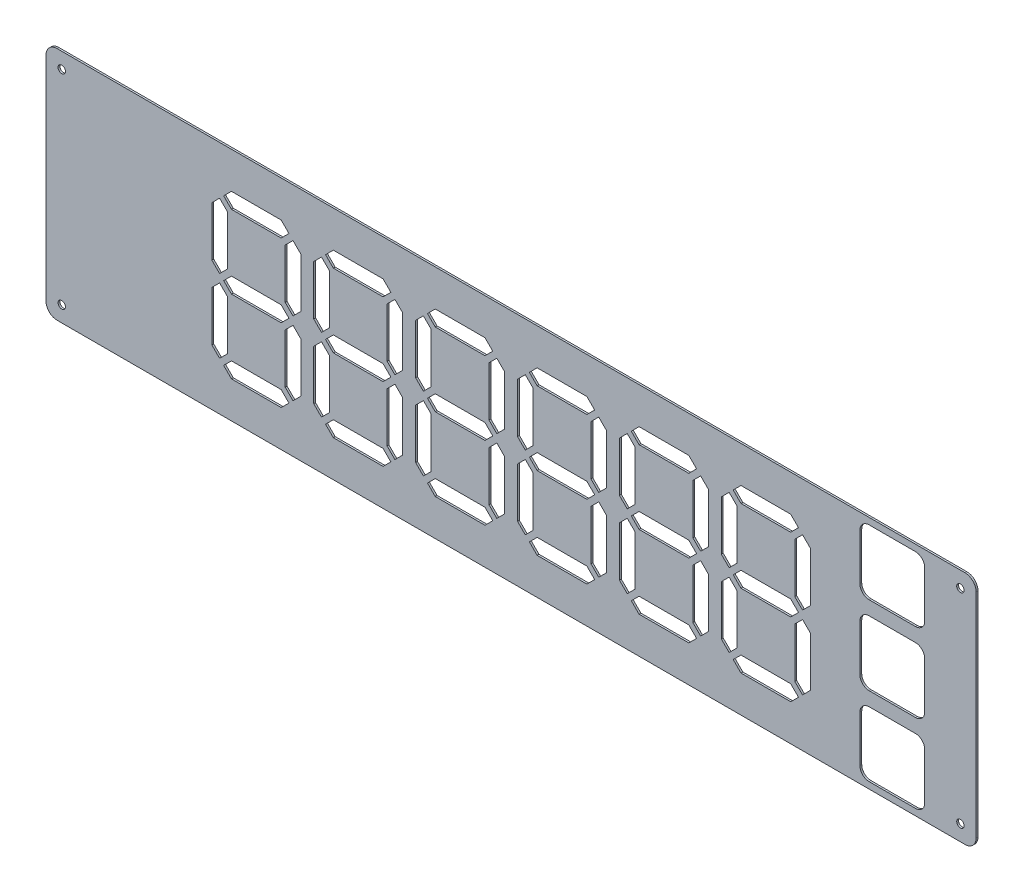
SolidWorks part; units mm, degrees
ref_plane "Plan de face" through (0, 0, 0) normal (0, 0, 1) x (1, 0, 0)
ref_plane "Plan de dessus" through (0, 0, 0) normal (0, 1, 0) x (1, 0, 0)
ref_plane "Plan de droite" through (0, 0, 0) normal (1, 0, 0) x (0, 0, -1)
sketch "Esquisse1" plane through (0, 0, 0) normal (0, 0, 1) x (1, 0, 0)
  line L0 (-107.7211, 8.5372) -> (517.2789, 8.5372) construction
  line L1 (204.7789, 142.0715) -> (204.7789, -117.1883) construction
  line L2 (694.7789, 135.5372) -> (-285.2211, 135.5372)
  line L7 (699.6693, -115.1854) -> (-290.1116, 132.2598) construction
  line L8 (699.6693, 132.2598) -> (-290.1116, -115.1854) construction
  line L9 (-297.2211, -106.4628) -> (-297.2211, 123.5372)
  line L10 (694.7789, -118.4628) -> (-285.2211, -118.4628)
  line L11 (706.7789, -106.4628) -> (706.7789, 123.5372)
  line L20 (-34.9839, 87.7798) -> (-43.3839, 96.1798)
  line L21 (-43.3839, 96.1798) -> (-97.0584, 96.1798)
  line L22 (-97.0584, 96.1798) -> (-105.4584, 87.7798)
  line L23 (-105.4584, 87.7798) -> (-97.0584, 79.3798)
  line L24 (-97.0584, 79.3798) -> (-43.3839, 79.3798)
  line L25 (-43.3839, 79.3798) -> (-34.9839, 87.7798)
  line L56 (-34.9839, -70.7055) -> (-43.3839, -62.3055)
  line L57 (-43.3839, -62.3055) -> (-97.0584, -62.3055)
  line L58 (-97.0584, -62.3055) -> (-105.4584, -70.7055)
  line L59 (-105.4584, -70.7055) -> (-97.0584, -79.1055)
  line L60 (-97.0584, -79.1055) -> (-43.3839, -79.1055)
  line L61 (-43.3839, -79.1055) -> (-34.9839, -70.7055)
  line L62 (-109.8425, 4.1531) -> (-118.2425, -4.2469)
  line L63 (-118.2425, -4.2469) -> (-118.2425, -57.9214)
  line L64 (-118.2425, -57.9214) -> (-109.8425, -66.3214)
  line L65 (-109.8425, -66.3214) -> (-101.4425, -57.9214)
  line L66 (-101.4425, -57.9214) -> (-101.4425, -4.2469)
  line L67 (-101.4425, -4.2469) -> (-109.8425, 4.1531)
  line L68 (-30.5998, 4.1531) -> (-38.9998, -4.2469)
  line L69 (-38.9998, -4.2469) -> (-38.9998, -57.9214)
  line L70 (-38.9998, -57.9214) -> (-30.5998, -66.3214)
  line L71 (-30.5998, -66.3214) -> (-22.1998, -57.9214)
  line L72 (-22.1998, -57.9214) -> (-22.1998, -4.2469)
  line L73 (-22.1998, -4.2469) -> (-30.5998, 4.1531)
  line L74 (-30.5998, 83.3957) -> (-38.9998, 74.9957)
  line L75 (-38.9998, 74.9957) -> (-38.9998, 21.3212)
  line L76 (-38.9998, 21.3212) -> (-30.5998, 12.9212)
  line L77 (-30.5998, 12.9212) -> (-22.1998, 21.3212)
  line L78 (-22.1998, 21.3212) -> (-22.1998, 74.9957)
  line L79 (-22.1998, 74.9957) -> (-30.5998, 83.3957)
  line L80 (-34.9839, 8.5372) -> (-43.3839, 16.9372)
  line L81 (-43.3839, 16.9372) -> (-97.0584, 16.9372)
  line L82 (-97.0584, 16.9372) -> (-105.4584, 8.5372)
  line L83 (-105.4584, 8.5372) -> (-97.0584, 0.1372)
  line L84 (-97.0584, 0.1372) -> (-43.3839, 0.1372)
  line L85 (-43.3839, 0.1372) -> (-34.9839, 8.5372)
  line L86 (-109.8425, 83.3957) -> (-118.2425, 74.9957)
  line L87 (-118.2425, 74.9957) -> (-118.2425, 21.3212)
  line L88 (-118.2425, 21.3212) -> (-109.8425, 12.9212)
  line L89 (-109.8425, 12.9212) -> (-101.4425, 21.3212)
  line L90 (-101.4425, 21.3212) -> (-101.4425, 74.9957)
  line L91 (-101.4425, 74.9957) -> (-109.8425, 83.3957)
  line L302 (515.0161, -70.7055) -> (506.6161, -62.3055)
  line L303 (506.6161, -62.3055) -> (452.9416, -62.3055)
  line L304 (452.9416, -62.3055) -> (444.5416, -70.7055)
  line L305 (444.5416, -70.7055) -> (452.9416, -79.1055)
  line L306 (452.9416, -79.1055) -> (506.6161, -79.1055)
  line L307 (506.6161, -79.1055) -> (515.0161, -70.7055)
  line L308 (519.4002, 4.1531) -> (511.0002, -4.2469)
  line L309 (511.0002, -4.2469) -> (511.0002, -57.9214)
  line L310 (511.0002, -57.9214) -> (519.4002, -66.3214)
  line L311 (519.4002, -66.3214) -> (527.8002, -57.9214)
  line L312 (527.8002, -57.9214) -> (527.8002, -4.2469)
  line L313 (527.8002, -4.2469) -> (519.4002, 4.1531)
  line L314 (519.4002, 83.3957) -> (511.0002, 74.9957)
  line L315 (511.0002, 74.9957) -> (511.0002, 21.3212)
  line L316 (511.0002, 21.3212) -> (519.4002, 12.9212)
  line L317 (519.4002, 12.9212) -> (527.8002, 21.3212)
  line L318 (527.8002, 21.3212) -> (527.8002, 74.9957)
  line L319 (527.8002, 74.9957) -> (519.4002, 83.3957)
  line L320 (515.0161, 8.5372) -> (506.6161, 16.9372)
  line L321 (506.6161, 16.9372) -> (452.9416, 16.9372)
  line L322 (452.9416, 16.9372) -> (444.5416, 8.5372)
  line L323 (444.5416, 8.5372) -> (452.9416, 0.1372)
  line L324 (452.9416, 0.1372) -> (506.6161, 0.1372)
  line L325 (506.6161, 0.1372) -> (515.0161, 8.5372)
  line L326 (515.0161, 87.7798) -> (506.6161, 96.1798)
  line L327 (506.6161, 96.1798) -> (452.9416, 96.1798)
  line L328 (452.9416, 96.1798) -> (444.5416, 87.7798)
  line L329 (444.5416, 87.7798) -> (452.9416, 79.3798)
  line L330 (452.9416, 79.3798) -> (506.6161, 79.3798)
  line L331 (506.6161, 79.3798) -> (515.0161, 87.7798)
  line L332 (440.1575, 83.3957) -> (431.7575, 74.9957)
  line L333 (431.7575, 74.9957) -> (431.7575, 21.3212)
  line L334 (431.7575, 21.3212) -> (440.1575, 12.9212)
  line L335 (440.1575, 12.9212) -> (448.5575, 21.3212)
  line L336 (448.5575, 21.3212) -> (448.5575, 74.9957)
  line L337 (448.5575, 74.9957) -> (440.1575, 83.3957)
  line L338 (440.1575, 4.1531) -> (431.7575, -4.2469)
  line L339 (431.7575, -4.2469) -> (431.7575, -57.9214)
  line L340 (431.7575, -57.9214) -> (440.1575, -66.3214)
  line L341 (440.1575, -66.3214) -> (448.5575, -57.9214)
  line L342 (448.5575, -57.9214) -> (448.5575, -4.2469)
  line L343 (448.5575, -4.2469) -> (440.1575, 4.1531)
  line L344 (405.0161, -70.7055) -> (396.6161, -62.3055)
  line L345 (396.6161, -62.3055) -> (342.9416, -62.3055)
  line L346 (342.9416, -62.3055) -> (334.5416, -70.7055)
  line L347 (334.5416, -70.7055) -> (342.9416, -79.1055)
  line L348 (342.9416, -79.1055) -> (396.6161, -79.1055)
  line L349 (396.6161, -79.1055) -> (405.0161, -70.7055)
  line L350 (409.4002, 4.1531) -> (401.0002, -4.2469)
  line L351 (401.0002, -4.2469) -> (401.0002, -57.9214)
  line L352 (401.0002, -57.9214) -> (409.4002, -66.3214)
  line L353 (409.4002, -66.3214) -> (417.8002, -57.9214)
  line L354 (417.8002, -57.9214) -> (417.8002, -4.2469)
  line L355 (417.8002, -4.2469) -> (409.4002, 4.1531)
  line L356 (330.1575, 4.1531) -> (321.7575, -4.2469)
  line L357 (321.7575, -4.2469) -> (321.7575, -57.9214)
  line L358 (321.7575, -57.9214) -> (330.1575, -66.3214)
  line L359 (330.1575, -66.3214) -> (338.5575, -57.9214)
  line L360 (338.5575, -57.9214) -> (338.5575, -4.2469)
  line L361 (338.5575, -4.2469) -> (330.1575, 4.1531)
  line L362 (405.0161, 8.5372) -> (396.6161, 16.9372)
  line L363 (396.6161, 16.9372) -> (342.9416, 16.9372)
  line L364 (342.9416, 16.9372) -> (334.5416, 8.5372)
  line L365 (334.5416, 8.5372) -> (342.9416, 0.1372)
  line L366 (342.9416, 0.1372) -> (396.6161, 0.1372)
  line L367 (396.6161, 0.1372) -> (405.0161, 8.5372)
  line L368 (409.4002, 83.3957) -> (401.0002, 74.9957)
  line L369 (401.0002, 74.9957) -> (401.0002, 21.3212)
  line L370 (401.0002, 21.3212) -> (409.4002, 12.9212)
  line L371 (409.4002, 12.9212) -> (417.8002, 21.3212)
  line L372 (417.8002, 21.3212) -> (417.8002, 74.9957)
  line L373 (417.8002, 74.9957) -> (409.4002, 83.3957)
  line L374 (405.0161, 87.7798) -> (396.6161, 96.1798)
  line L375 (396.6161, 96.1798) -> (342.9416, 96.1798)
  line L376 (342.9416, 96.1798) -> (334.5416, 87.7798)
  line L377 (334.5416, 87.7798) -> (342.9416, 79.3798)
  line L378 (342.9416, 79.3798) -> (396.6161, 79.3798)
  line L379 (396.6161, 79.3798) -> (405.0161, 87.7798)
  line L380 (330.1575, 83.3957) -> (321.7575, 74.9957)
  line L381 (321.7575, 74.9957) -> (321.7575, 21.3212)
  line L382 (321.7575, 21.3212) -> (330.1575, 12.9212)
  line L383 (330.1575, 12.9212) -> (338.5575, 21.3212)
  line L384 (338.5575, 21.3212) -> (338.5575, 74.9957)
  line L385 (338.5575, 74.9957) -> (330.1575, 83.3957)
  line L386 (220.1575, 4.1531) -> (211.7575, -4.2469)
  line L387 (211.7575, -4.2469) -> (211.7575, -57.9214)
  line L388 (211.7575, -57.9214) -> (220.1575, -66.3214)
  line L389 (220.1575, -66.3214) -> (228.5575, -57.9214)
  line L390 (228.5575, -57.9214) -> (228.5575, -4.2469)
  line L391 (228.5575, -4.2469) -> (220.1575, 4.1531)
  line L392 (295.0161, -70.7055) -> (286.6161, -62.3055)
  line L393 (286.6161, -62.3055) -> (232.9416, -62.3055)
  line L394 (232.9416, -62.3055) -> (224.5416, -70.7055)
  line L395 (224.5416, -70.7055) -> (232.9416, -79.1055)
  line L396 (232.9416, -79.1055) -> (286.6161, -79.1055)
  line L397 (286.6161, -79.1055) -> (295.0161, -70.7055)
  line L398 (299.4002, 4.1531) -> (291.0002, -4.2469)
  line L399 (291.0002, -4.2469) -> (291.0002, -57.9214)
  line L400 (291.0002, -57.9214) -> (299.4002, -66.3214)
  line L401 (299.4002, -66.3214) -> (307.8002, -57.9214)
  line L402 (307.8002, -57.9214) -> (307.8002, -4.2469)
  line L403 (307.8002, -4.2469) -> (299.4002, 4.1531)
  line L404 (299.4002, 83.3957) -> (291.0002, 74.9957)
  line L405 (291.0002, 74.9957) -> (291.0002, 21.3212)
  line L406 (291.0002, 21.3212) -> (299.4002, 12.9212)
  line L407 (299.4002, 12.9212) -> (307.8002, 21.3212)
  line L408 (307.8002, 21.3212) -> (307.8002, 74.9957)
  line L409 (307.8002, 74.9957) -> (299.4002, 83.3957)
  line L410 (295.0161, 8.5372) -> (286.6161, 16.9372)
  line L411 (286.6161, 16.9372) -> (232.9416, 16.9372)
  line L412 (232.9416, 16.9372) -> (224.5416, 8.5372)
  line L413 (224.5416, 8.5372) -> (232.9416, 0.1372)
  line L414 (232.9416, 0.1372) -> (286.6161, 0.1372)
  line L415 (286.6161, 0.1372) -> (295.0161, 8.5372)
  line L416 (220.1575, 83.3957) -> (211.7575, 74.9957)
  line L417 (211.7575, 74.9957) -> (211.7575, 21.3212)
  line L418 (211.7575, 21.3212) -> (220.1575, 12.9212)
  line L419 (220.1575, 12.9212) -> (228.5575, 21.3212)
  line L420 (228.5575, 21.3212) -> (228.5575, 74.9957)
  line L421 (228.5575, 74.9957) -> (220.1575, 83.3957)
  line L422 (295.0161, 87.7798) -> (286.6161, 96.1798)
  line L423 (286.6161, 96.1798) -> (232.9416, 96.1798)
  line L424 (232.9416, 96.1798) -> (224.5416, 87.7798)
  line L425 (224.5416, 87.7798) -> (232.9416, 79.3798)
  line L426 (232.9416, 79.3798) -> (286.6161, 79.3798)
  line L427 (286.6161, 79.3798) -> (295.0161, 87.7798)
  line L428 (110.1575, 4.1531) -> (101.7575, -4.2469)
  line L429 (101.7575, -4.2469) -> (101.7575, -57.9214)
  line L430 (101.7575, -57.9214) -> (110.1575, -66.3214)
  line L431 (110.1575, -66.3214) -> (118.5575, -57.9214)
  line L432 (118.5575, -57.9214) -> (118.5575, -4.2469)
  line L433 (118.5575, -4.2469) -> (110.1575, 4.1531)
  line L434 (185.0161, -70.7055) -> (176.6161, -62.3055)
  line L435 (176.6161, -62.3055) -> (122.9416, -62.3055)
  line L436 (122.9416, -62.3055) -> (114.5416, -70.7055)
  line L437 (114.5416, -70.7055) -> (122.9416, -79.1055)
  line L438 (122.9416, -79.1055) -> (176.6161, -79.1055)
  line L439 (176.6161, -79.1055) -> (185.0161, -70.7055)
  line L440 (189.4002, 4.1531) -> (181.0002, -4.2469)
  line L441 (181.0002, -4.2469) -> (181.0002, -57.9214)
  line L442 (181.0002, -57.9214) -> (189.4002, -66.3214)
  line L443 (189.4002, -66.3214) -> (197.8002, -57.9214)
  line L444 (197.8002, -57.9214) -> (197.8002, -4.2469)
  line L445 (197.8002, -4.2469) -> (189.4002, 4.1531)
  line L446 (189.4002, 83.3957) -> (181.0002, 74.9957)
  line L447 (181.0002, 74.9957) -> (181.0002, 21.3212)
  line L448 (181.0002, 21.3212) -> (189.4002, 12.9212)
  line L449 (189.4002, 12.9212) -> (197.8002, 21.3212)
  line L450 (197.8002, 21.3212) -> (197.8002, 74.9957)
  line L451 (197.8002, 74.9957) -> (189.4002, 83.3957)
  line L452 (185.0161, 87.7798) -> (176.6161, 96.1798)
  line L453 (176.6161, 96.1798) -> (122.9416, 96.1798)
  line L454 (122.9416, 96.1798) -> (114.5416, 87.7798)
  line L455 (114.5416, 87.7798) -> (122.9416, 79.3798)
  line L456 (122.9416, 79.3798) -> (176.6161, 79.3798)
  line L457 (176.6161, 79.3798) -> (185.0161, 87.7798)
  line L458 (110.1575, 83.3957) -> (101.7575, 74.9957)
  line L459 (101.7575, 74.9957) -> (101.7575, 21.3212)
  line L460 (101.7575, 21.3212) -> (110.1575, 12.9212)
  line L461 (110.1575, 12.9212) -> (118.5575, 21.3212)
  line L462 (118.5575, 21.3212) -> (118.5575, 74.9957)
  line L463 (118.5575, 74.9957) -> (110.1575, 83.3957)
  line L464 (185.0161, 8.5372) -> (176.6161, 16.9372)
  line L465 (176.6161, 16.9372) -> (122.9416, 16.9372)
  line L466 (122.9416, 16.9372) -> (114.5416, 8.5372)
  line L467 (114.5416, 8.5372) -> (122.9416, 0.1372)
  line L468 (122.9416, 0.1372) -> (176.6161, 0.1372)
  line L469 (176.6161, 0.1372) -> (185.0161, 8.5372)
  line L470 (75.0161, -70.7055) -> (66.6161, -62.3055)
  line L471 (66.6161, -62.3055) -> (12.9416, -62.3055)
  line L472 (12.9416, -62.3055) -> (4.5416, -70.7055)
  line L473 (4.5416, -70.7055) -> (12.9416, -79.1055)
  line L474 (12.9416, -79.1055) -> (66.6161, -79.1055)
  line L475 (66.6161, -79.1055) -> (75.0161, -70.7055)
  line L476 (0.1575, 4.1531) -> (-8.2425, -4.2469)
  line L477 (-8.2425, -4.2469) -> (-8.2425, -57.9214)
  line L478 (-8.2425, -57.9214) -> (0.1575, -66.3214)
  line L479 (0.1575, -66.3214) -> (8.5575, -57.9214)
  line L480 (8.5575, -57.9214) -> (8.5575, -4.2469)
  line L481 (8.5575, -4.2469) -> (0.1575, 4.1531)
  line L482 (79.4002, 4.1531) -> (71.0002, -4.2469)
  line L483 (71.0002, -4.2469) -> (71.0002, -57.9214)
  line L484 (71.0002, -57.9214) -> (79.4002, -66.3214)
  line L485 (79.4002, -66.3214) -> (87.8002, -57.9214)
  line L486 (87.8002, -57.9214) -> (87.8002, -4.2469)
  line L487 (87.8002, -4.2469) -> (79.4002, 4.1531)
  line L488 (75.0161, 8.5372) -> (66.6161, 16.9372)
  line L489 (66.6161, 16.9372) -> (12.9416, 16.9372)
  line L490 (12.9416, 16.9372) -> (4.5416, 8.5372)
  line L491 (4.5416, 8.5372) -> (12.9416, 0.1372)
  line L492 (12.9416, 0.1372) -> (66.6161, 0.1372)
  line L493 (66.6161, 0.1372) -> (75.0161, 8.5372)
  line L494 (79.4002, 83.3957) -> (71.0002, 74.9957)
  line L495 (71.0002, 74.9957) -> (71.0002, 21.3212)
  line L496 (71.0002, 21.3212) -> (79.4002, 12.9212)
  line L497 (79.4002, 12.9212) -> (87.8002, 21.3212)
  line L498 (87.8002, 21.3212) -> (87.8002, 74.9957)
  line L499 (87.8002, 74.9957) -> (79.4002, 83.3957)
  line L500 (0.1575, 83.3957) -> (-8.2425, 74.9957)
  line L501 (-8.2425, 74.9957) -> (-8.2425, 21.3212)
  line L502 (-8.2425, 21.3212) -> (0.1575, 12.9212)
  line L503 (0.1575, 12.9212) -> (8.5575, 21.3212)
  line L504 (8.5575, 21.3212) -> (8.5575, 74.9957)
  line L505 (8.5575, 74.9957) -> (0.1575, 83.3957)
  line L506 (75.0161, 87.7798) -> (66.6161, 96.1798)
  line L507 (66.6161, 96.1798) -> (12.9416, 96.1798)
  line L508 (12.9416, 96.1798) -> (4.5416, 87.7798)
  line L509 (4.5416, 87.7798) -> (12.9416, 79.3798)
  line L510 (12.9416, 79.3798) -> (66.6161, 79.3798)
  line L511 (66.6161, 79.3798) -> (75.0161, 87.7798)
  line L512 (527.8002, 133.5372) -> (527.8002, -116.4628) construction
  line L513 (527.8002, 8.5372) -> (704.7789, 8.5372) construction
  line L514 (616.2895, 133.5372) -> (616.2895, -116.4628) construction
  line L515 (579.0473, 51.0372) -> (658.1055, 51.0372) construction
  line L516 (641.2895, -26.4628) -> (591.2895, -26.4628)
  line L517 (651.2895, -16.4628) -> (651.2895, 33.5372)
  line L518 (641.2895, 43.5372) -> (591.2895, 43.5372)
  line L519 (581.2895, -16.4628) -> (581.2895, 33.5372)
  line L520 (651.2895, -26.4628) -> (581.2895, 43.5372) construction
  line L521 (651.2895, 43.5372) -> (581.2895, -26.4628) construction
  line L522 (581.2895, 118.5372) -> (581.2895, 68.5372)
  line L523 (641.2895, 128.5372) -> (591.2895, 128.5372)
  line L524 (651.2895, 118.5372) -> (651.2895, 68.5372)
  line L525 (641.2895, 58.5372) -> (591.2895, 58.5372)
  line L526 (581.2895, -101.4628) -> (581.2895, -51.4628)
  line L527 (641.2895, -41.4628) -> (591.2895, -41.4628)
  line L528 (651.2895, -101.4628) -> (651.2895, -51.4628)
  line L529 (641.2895, -111.4628) -> (591.2895, -111.4628)
  arc A0 (651.2895, 33.5372) -> (641.2895, 43.5372) centre (641.2895, 33.5372) ccw
  arc A1 (651.2895, -16.4628) -> (641.2895, -26.4628) centre (641.2895, -16.4628) cw
  arc A2 (591.2895, -26.4628) -> (581.2895, -16.4628) centre (591.2895, -16.4628) cw
  arc A3 (581.2895, 33.5372) -> (591.2895, 43.5372) centre (591.2895, 33.5372) cw
  arc A4 (581.2895, 68.5372) -> (591.2895, 58.5372) centre (591.2895, 68.5372) ccw
  arc A5 (591.2895, 128.5372) -> (581.2895, 118.5372) centre (591.2895, 118.5372) ccw
  arc A6 (651.2895, 118.5372) -> (641.2895, 128.5372) centre (641.2895, 118.5372) ccw
  arc A7 (651.2895, 68.5372) -> (641.2895, 58.5372) centre (641.2895, 68.5372) cw
  arc A8 (591.2895, -111.4628) -> (581.2895, -101.4628) centre (591.2895, -101.4628) cw
  arc A9 (581.2895, -51.4628) -> (591.2895, -41.4628) centre (591.2895, -51.4628) cw
  arc A10 (651.2895, -51.4628) -> (641.2895, -41.4628) centre (641.2895, -51.4628) ccw
  arc A11 (651.2895, -101.4628) -> (641.2895, -111.4628) centre (641.2895, -101.4628) cw
  arc A16 (-297.2211, 123.5372) -> (-285.2211, 135.5372) centre (-285.2211, 123.5372) cw
  arc A17 (-285.2211, -118.4628) -> (-297.2211, -106.4628) centre (-285.2211, -106.4628) cw
  arc A18 (694.7789, -118.4628) -> (706.7789, -106.4628) centre (694.7789, -106.4628) ccw
  arc A19 (706.7789, 123.5372) -> (694.7789, 135.5372) centre (694.7789, 123.5372) ccw
  point P6 (204.7789, 8.5372)
  point P269 (616.2895, 8.5372)
  dimension "D6" = 10
  dimension "D4" = 70
  dimension "D5" = 70
  dimension "D7" = 42.5
extrude "Boss.-Extru.1" add sketch "Esquisse1" along normal blind 2
sketch "Esquisse2" plane through (0, 0, 0) normal (0, 0, -1) x (-1, 0, 0)
  line L4 (-706.7789, 123.5372) -> (-706.7789, -106.4628)
  line L5 (-694.7789, -118.4628) -> (285.2211, -118.4628)
  line L6 (297.2211, -106.4628) -> (297.2211, 123.5372)
  line L7 (285.2211, 135.5372) -> (-694.7789, 135.5372)
  line L8 (-706.7789, 123.5372) -> (-706.7789, -106.4628)
  line L9 (-694.7789, -118.4628) -> (285.2211, -118.4628)
  line L10 (297.2211, -106.4628) -> (297.2211, 123.5372)
  line L11 (285.2211, 135.5372) -> (-694.7789, 135.5372)
  circle A0 centre (-689.7789, 118.5372) radius 4
  circle A1 centre (280.2211, 118.5372) radius 4
  circle A2 centre (280.2211, -101.4628) radius 4
  circle A3 centre (-689.7789, -101.4628) radius 4
  arc A4 (-694.7789, 135.5372) -> (-706.7789, 123.5372) centre (-694.7789, 123.5372) ccw
  arc A5 (-706.7789, -106.4628) -> (-694.7789, -118.4628) centre (-694.7789, -106.4628) ccw
  arc A6 (285.2211, -118.4628) -> (297.2211, -106.4628) centre (285.2211, -106.4628) ccw
  arc A7 (297.2211, 123.5372) -> (285.2211, 135.5372) centre (285.2211, 123.5372) ccw
  arc A8 (-694.7789, 135.5372) -> (-706.7789, 123.5372) centre (-694.7789, 123.5372) ccw
  arc A9 (-706.7789, -106.4628) -> (-694.7789, -118.4628) centre (-694.7789, -106.4628) ccw
  arc A10 (285.2211, -118.4628) -> (297.2211, -106.4628) centre (285.2211, -106.4628) ccw
  arc A11 (297.2211, 123.5372) -> (285.2211, 135.5372) centre (285.2211, 123.5372) ccw
  dimension "D1" = 0
extrude "Enlèv. mat.-Extru.2" cut sketch "Esquisse2" against normal blind 38 contours A3 | A0 | A1 | A2
